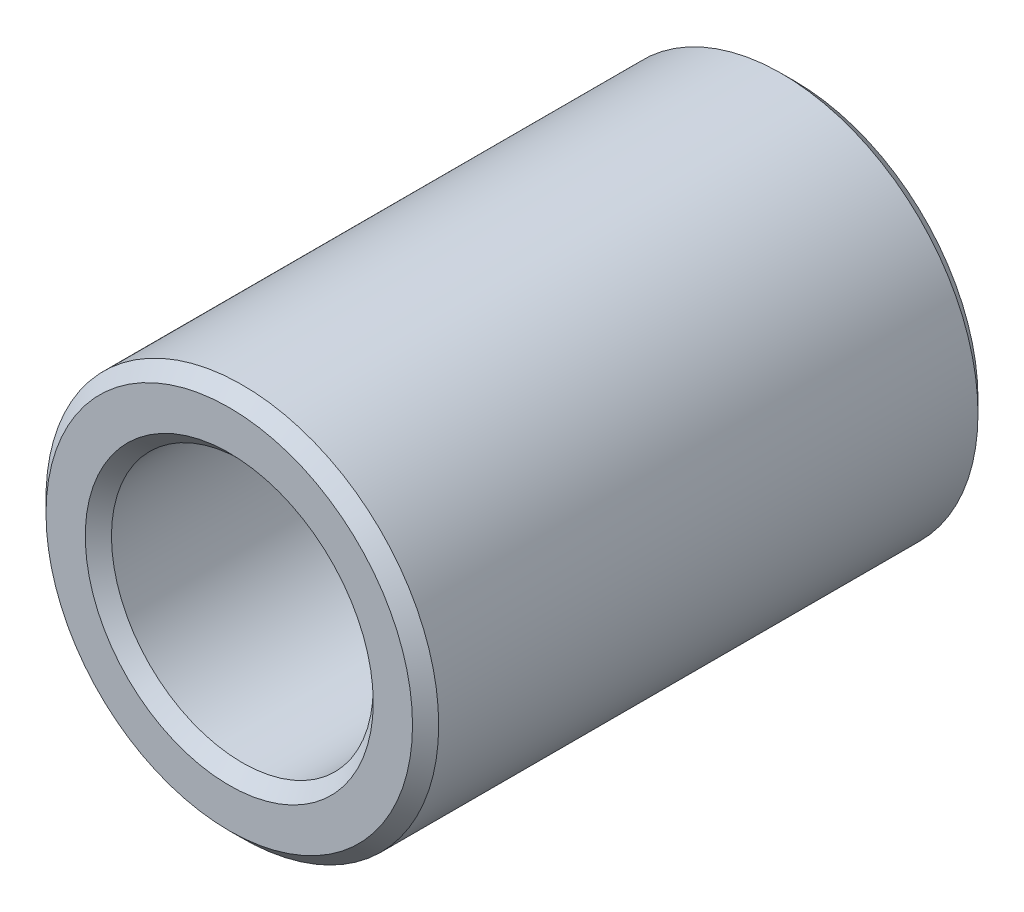
SolidWorks part; units mm, degrees
material "Messing"
ref_plane "Ebene vorne" through (0, 0, 0) normal (0, 0, 1) x (1, 0, 0)
ref_plane "Ebene oben" through (0, 0, 0) normal (0, 1, 0) x (1, 0, 0)
ref_plane "Ebene rechts" through (0, 0, 0) normal (1, 0, 0) x (0, 0, -1)
sketch "Skizze1" plane through (0, 0, 0) normal (0, 0, 1) x (1, 0, 0)
  circle A0 centre (0, 0) radius 1.5
  circle A1 centre (0, 0) radius 1
  dimension "D1" = 3
  dimension "D2" = 2
extrude "Aufsatz-Linear austragen1" add sketch "Skizze1" along normal blind 4.32
chamfer "Fase1" distance 0.1 angle 45 4 edges at (1, 0, 0) (1.5, 0, 0) (1, 0, 4.32) (1.5, 0, 4.32)
